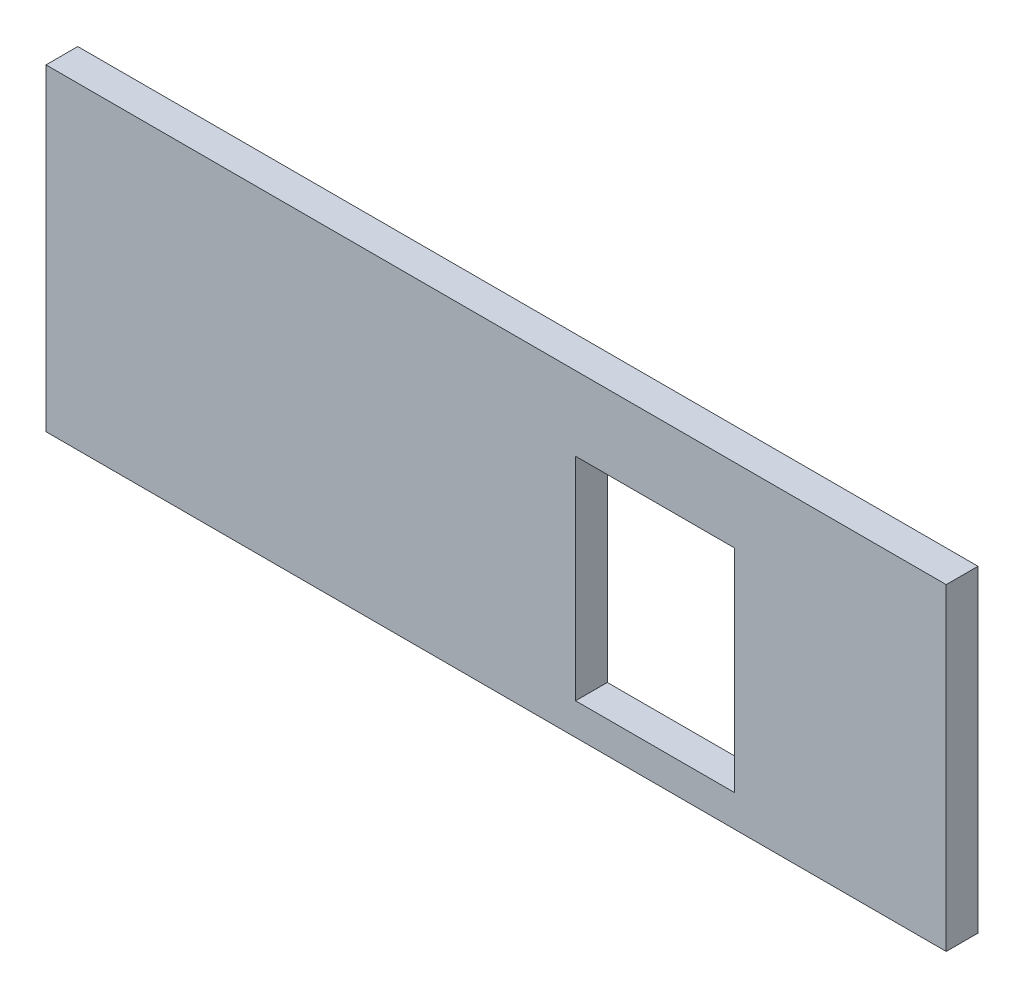
SolidWorks part; units mm, degrees
ref_plane "Front Plane" through (0, 0, 0) normal (0, 0, 1) x (1, 0, 0)
ref_plane "Top Plane" through (0, 0, 0) normal (0, 1, 0) x (1, 0, 0)
ref_plane "Right Plane" through (0, 0, 0) normal (1, 0, 0) x (0, 0, -1)
sketch "Sketch1" plane through (0, 0, 0) normal (0, 0, 1) x (1, 0, 0)
  line L1 (0, 0) -> (170, 0)
  line L2 (0, 0) -> (0, 60)
  line L3 (0, 60) -> (170, 60)
  line L4 (170, 0) -> (170, 60)
  dimension "D1" = 170
  dimension "D2" = 60
extrude "Boss-Extrude1" add sketch "Sketch1" along normal blind 6
sketch "Sketch2" plane through (0, 0, 6) normal (0, 0, 1) x (1, 0, 0)
  line L0 (170, 0) -> (170, 60) construction
  line L1 (100, 46) -> (130, 46)
  line L2 (100, 46) -> (100, 6)
  line L3 (100, 6) -> (130, 6)
  line L4 (130, 46) -> (130, 6)
  line L5 (0, 0) -> (170, 0) construction
  dimension "D1" = 40
  dimension "D2" = 30
  dimension "D3" = 40
  dimension "D4" = 6
extrude "Cut-Extrude1" cut sketch "Sketch2" against normal through all
